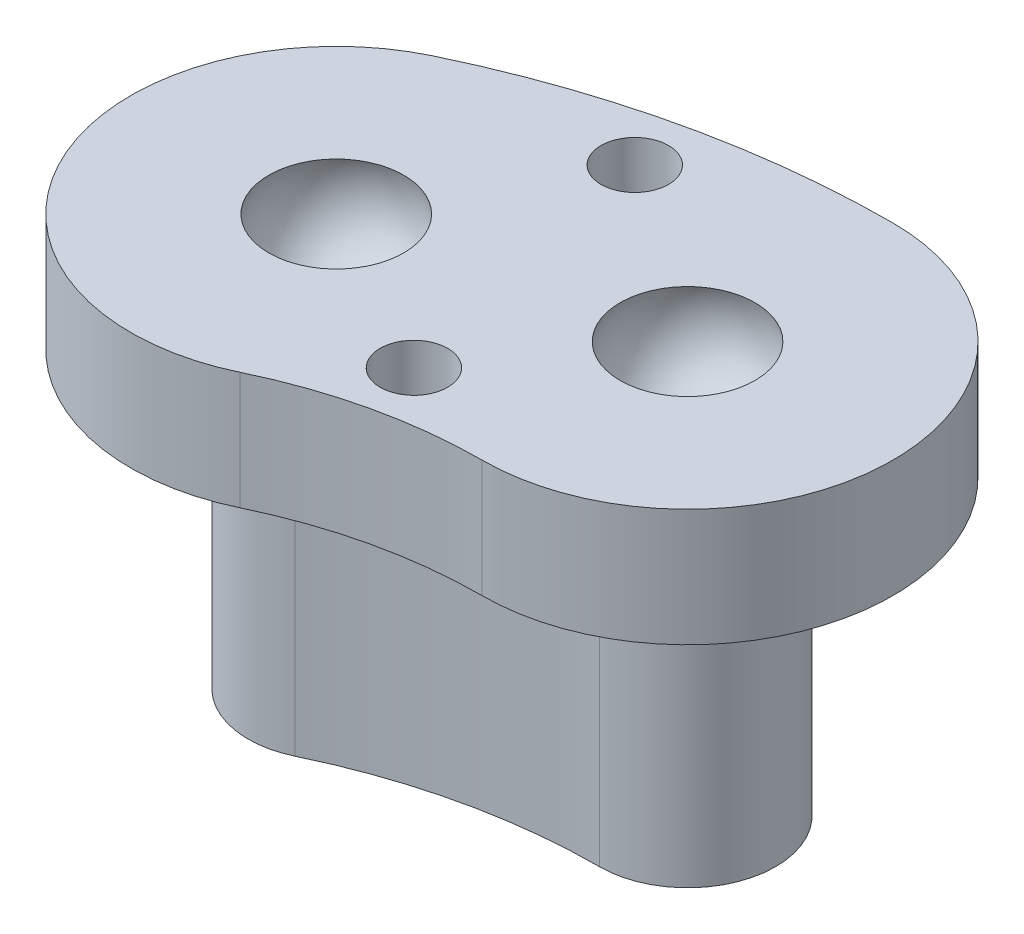
SolidWorks part; units mm, degrees
ref_plane "前视基准面" through (0, 0, 0) normal (0, 0, 1) x (1, 0, 0)
ref_plane "上视基准面" through (0, 0, 0) normal (0, 1, 0) x (1, 0, 0)
ref_plane "右视基准面" through (0, 0, 0) normal (1, 0, 0) x (0, 0, -1)
sketch "草图1" plane through (0, 0, 0) normal (0, 1, 0) x (1, 0, 0)
  line L0 (-9.75, 20.2778) -> (0, 0) construction
  line L1 (0, 22.5) -> (0, 0) construction
  circle A0 centre (0, 0) radius 22.5 construction
  arc A1 (0, 22.5) -> (-9.75, 20.2778) centre (0, 0) ccw construction
  arc A2 (0, 25.5) -> (-11.05, 22.9815) centre (0, 0) ccw
  arc A3 (0, 19.5) -> (-8.45, 17.5741) centre (0, 0) ccw
  arc A4 (0, 19.5) -> (0, 25.5) centre (0, 22.5) ccw
  arc A5 (-11.05, 22.9815) -> (-8.45, 17.5741) centre (-9.75, 20.2778) ccw
  point P5 (-5, 21.9374)
  dimension "D1" = 45
  dimension "D2" = 3
  dimension "D3" = 10
extrude "凸台-拉伸1" add sketch "草图1" along normal blind 10
sketch "草图2" plane through (0, 10, 0) normal (0, 1, 0) x (1, 0, 0)
  arc A0 (-9.75, 20.2778) -> (0, 22.5) centre (0, 0) cw construction
  arc A1 (0, 29.5) -> (-12.7833, 26.5864) centre (0, 0) ccw
  arc A2 (0, 15.5) -> (-6.7166, 13.9691) centre (0, 0) ccw
  arc A3 (0, 15.5) -> (0, 29.5) centre (0, 22.5) ccw
  arc A4 (-12.7833, 26.5864) -> (-6.7166, 13.9691) centre (-9.75, 20.2778) ccw
  point P5 (-5, 21.9374)
  dimension "D1" = 7
extrude "凸台-拉伸2" add sketch "草图2" along normal blind 4
ref_plane "基准面1" through (0, 13.15, 0) normal (0, 1, 0) x (1, 0, 0)
sketch "草图3" plane through (0, 13.15, 0) normal (0, 1, 0) x (1, 0, 0)
  line L0 (-9.75, 22.7278) -> (-9.75, 17.8278)
  arc A0 (-9.75, 22.7278) -> (-9.75, 17.8278) centre (-9.75, 20.2778) ccw
  circle A1 centre (0, 22.5) radius 2.45 construction
  dimension "D1" = 4.9
  dimension "D2" = 4.9
revolve "切除-旋转1" cut sketch "草图3" angle 360 about L0
sketch "草图4" plane through (0, 13.15, 0) normal (0, 1, 0) x (1, 0, 0)
  line L0 (0, 24.95) -> (0, 20.05)
  arc A0 (0, 24.95) -> (0, 20.05) centre (0, 22.5) ccw
  dimension "D1" = 4.9
revolve "切除-旋转2" cut sketch "草图4" angle 360 about L0
ref_plane "基准面2" through (-4.225, 0, -18.537) normal (0.2222, 0, 0.975) x (0.975, 0, -0.2222)
sketch "草图5" plane through (-4.225, 0, -18.537) normal (0.2222, 0, 0.975) x (0.975, 0, -0.2222)
  line L0 (4.3333, 0) -> (8, 0) construction
  circle A0 centre (0, 4) radius 1.5
  dimension "D1" = 3
  dimension "D2" = 4
sketch "草图6" plane through (0, 14, 0) normal (0, 1, 0) x (1, 0, 0)
  line L0 (-6.5556, 28.7624) -> (-3.4444, 15.1124) construction
  arc A0 (0, 29.5) -> (-12.7833, 26.5864) centre (0, 0) ccw construction
  arc A1 (0, 15.5) -> (-6.7166, 13.9691) centre (0, 0) ccw construction
  circle A2 centre (-6.1111, 26.8124) radius 1.15
  circle A3 centre (-3.8889, 17.0624) radius 1.15
  dimension "D1" = 2.3
  dimension "D2" = 2.3
  dimension "D3" = 2
  dimension "D4" = 2
extrude "切除-拉伸2" cut sketch "草图6" against normal blind 10
